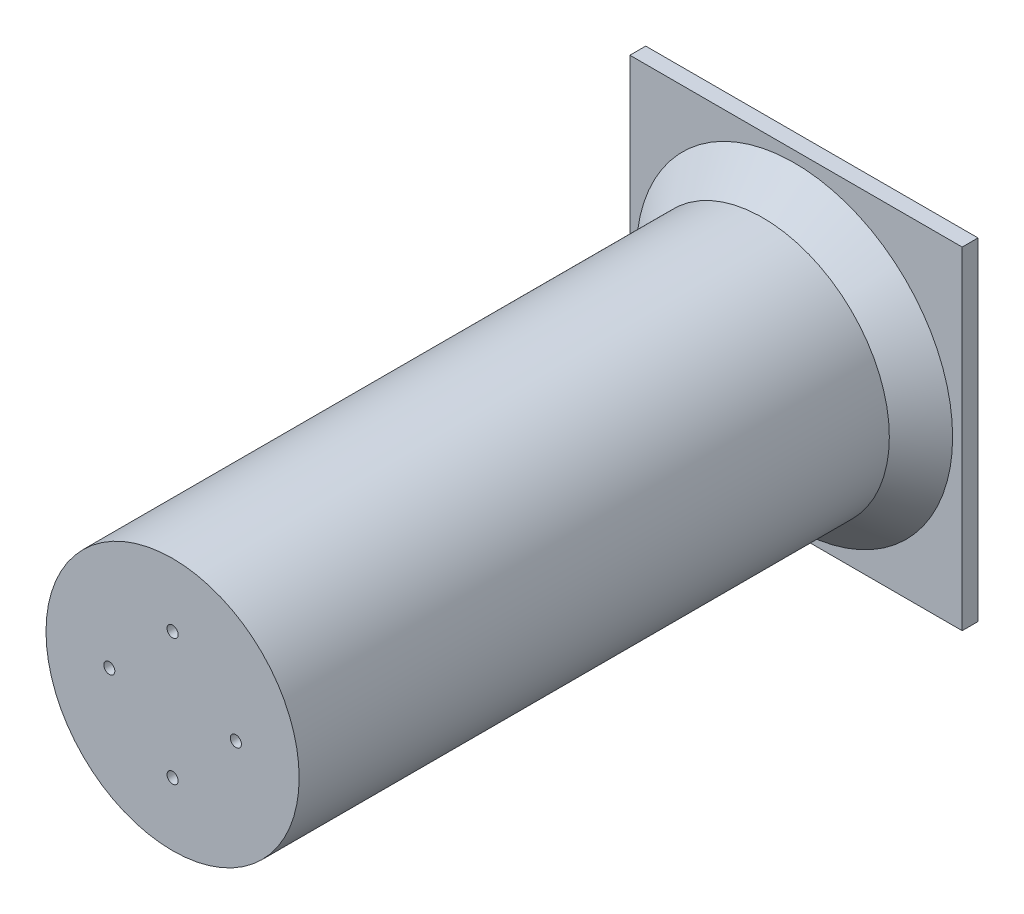
SolidWorks part; units mm, degrees
ref_plane "Alzado" through (0, 0, 0) normal (0, 0, 1) x (1, 0, 0)
ref_plane "Planta" through (0, 0, 0) normal (0, 1, 0) x (1, 0, 0)
ref_plane "Vista lateral" through (0, 0, 0) normal (1, 0, 0) x (0, 0, -1)
sketch "Croquis1" plane through (0, 0, 0) normal (0, 0, 1) x (1, 0, 0)
  line L1 (-117.2917, 97.7627) -> (131.4683, 97.7627)
  line L2 (-117.2917, 97.7627) -> (-117.2917, -97.2373)
  line L3 (-117.2917, -97.2373) -> (131.4683, -97.2373)
  line L4 (131.4683, 97.7627) -> (131.4683, -97.2373)
  dimension "D1" = 248.76
  dimension "D2" = 195
extrude "Saliente-Extruir1" add sketch "Croquis1" along normal blind 5
sketch "Croquis2" plane through (0, 0, 5) normal (0, 0, 1) x (1, 0, 0)
  line L0 (-117.2917, 0.2627) -> (131.4683, 0.2627) construction
  line L1 (-117.2917, 97.7627) -> (-117.2917, -97.2373) construction
  line L2 (131.4683, -97.2373) -> (131.4683, 97.7627) construction
  line L3 (-117.2917, -97.2373) -> (-69.2917, -97.2373)
  line L4 (-117.2917, -97.2373) -> (131.4683, -97.2373) construction
  line L5 (-69.2917, -97.2373) -> (-69.2917, -67.2373)
  line L6 (-69.2917, -67.2373) -> (-117.2917, -67.2373)
  line L7 (-117.2917, -67.2373) -> (-117.2917, -97.2373)
  line L8 (131.4683, 67.7627) -> (101.4683, 67.7627)
  line L9 (131.4683, -97.2373) -> (101.4683, -97.2373)
  line L10 (131.4683, -97.2373) -> (131.4683, -67.2373)
  line L11 (131.4683, -67.2373) -> (101.4683, -67.2373)
  line L12 (101.4683, -97.2373) -> (101.4683, -67.2373)
  line L13 (101.4683, 97.7627) -> (101.4683, 67.7627)
  line L14 (131.4683, 97.7627) -> (101.4683, 97.7627)
  line L15 (131.4683, 97.7627) -> (131.4683, 67.7627)
  line L16 (-69.2917, 67.7627) -> (-117.2917, 67.7627)
  line L17 (-69.2917, 97.7627) -> (-69.2917, 67.7627)
  line L18 (-117.2917, 97.7627) -> (-69.2917, 97.7627)
  line L19 (-117.2917, 67.7627) -> (-117.2917, 97.7627)
  dimension "D1" = 48
  dimension "D2" = 30
  dimension "D3" = 30
  dimension "D4" = 30
extrude "Cortar-Extruir1" cut sketch "Croquis2" against normal blind 2
sketch "Croquis3" plane through (0, 0, 5) normal (0, 0, 1) x (1, 0, 0)
  line L0 (-69.2917, 97.7627) -> (-117.2917, 97.7627) construction
  line L1 (116.4683, 83.7627) -> (116.4683, 67.7627) construction
  line L3 (116.4683, -83.2373) -> (116.4683, -67.2373) construction
  line L5 (131.4683, -67.2373) -> (101.4683, -67.2373) construction
  line L6 (101.4683, 67.7627) -> (131.4683, 67.7627) construction
  line L7 (-93.2917, 83.7627) -> (-93.2917, 67.7627) construction
  line L8 (-117.2917, 67.7627) -> (-69.2917, 67.7627) construction
  line L9 (-93.2917, -83.2373) -> (-93.2917, -67.2373) construction
  line L10 (-69.2917, -67.2373) -> (-117.2917, -67.2373) construction
  circle A0 centre (-93.2917, 83.7627) radius 2.375
  circle A1 centre (-93.2917, -83.2373) radius 2.375
  circle A2 centre (116.4683, 83.7627) radius 2.375
  circle A3 centre (116.4683, -83.2373) radius 2.375
  dimension "D2" = 4.75
  dimension "D3" = 4.75
  dimension "D5" = 4.75
  dimension "D6" = 4.75
  dimension "D1" = 14
  dimension "D4" = 14
  dimension "D7" = 209.76
  dimension "D8" = 16
  dimension "D9" = 16
extrude "Cortar-Extruir2" cut sketch "Croquis3" against normal blind 10
sketch "Croquis4" plane through (0, 0, 0) normal (0, 0, -1) x (-1, 0, 0)
  line L7 (-131.4683, 97.7627) -> (117.2917, 97.7627) construction
  line L9 (117.2917, 97.7627) -> (117.2917, -97.2373) construction
  circle A0 centre (55.1017, 0.2627) radius 40
  dimension "D3" = 80
  dimension "D1" = 62.19
  dimension "D2" = 97.5
extrude "Saliente-Extruir2" add sketch "Croquis4" along normal blind 196.5 contours A0
sketch "Croquis5" plane through (0, 0, 0) normal (0, 0, -1) x (-1, 0, 0)
  line L0 (-131.4683, 0.2627) -> (117.2917, 0.2627) construction
  line L1 (-131.4683, -97.2373) -> (-131.4683, 97.7627) construction
  line L2 (117.2917, 97.7627) -> (117.2917, -97.2373) construction
  circle A0 centre (-76.9683, 0.2627) radius 12.5
  dimension "D1" = 25
  dimension "D2" = 54.5
extrude "Cortar-Extruir3" cut sketch "Croquis5" against normal blind 10
sketch "Croquis6" plane through (0, 0, 0) normal (0, 0, -1) x (-1, 0, 0)
  line L0 (-131.4683, 97.7627) -> (117.2917, 97.7627) construction
  line L1 (-7.0883, 97.7627) -> (-7.0883, -97.2373)
  line L2 (117.2917, -97.2373) -> (-131.4683, -97.2373) construction
  line L3 (-7.0883, 97.7627) -> (117.2917, 97.7627)
  line L4 (117.2917, 97.7627) -> (117.2917, -97.2373)
  line L5 (117.2917, -97.2373) -> (-7.0883, -97.2373)
  line L6 (-131.4683, 0.2627) -> (56.0317, 0.2627)
  line L7 (-131.4683, -97.2373) -> (-131.4683, 97.7627) construction
  circle A1 centre (56.0317, 0.2627) radius 100
  dimension "D1" = 200
  dimension "D2" = 187.5
sketch "Croquis9" plane through (0, 97.7627, 0) normal (0, 1, 0) x (1, 0, 0)
  line L0 (7.0883, 0) -> (7.0883, -5)
  line L1 (131.4683, 0) -> (-117.2917, 0) construction
  line L2 (101.4683, -5) -> (-69.2917, -5) construction
ref_plane "Plano3" through (7.0883, 0, 0) normal (1, 0, 0) x (0, 0, -1)
sketch "Croquis12" plane through (7.0883, 0, 0) normal (1, 0, 0) x (0, 0, -1)
  line L0 (0, 97.7627) -> (0, 67.7627)
  line L1 (0, 67.7627) -> (12, 67.7627)
  line L2 (12, 67.7627) -> (12, 97.7627)
  line L3 (12, 97.7627) -> (0, 97.7627)
  line L4 (0, -97.2373) -> (12, -97.2373)
  line L5 (12, -97.2373) -> (12, -67.2373)
  line L6 (12, -67.2373) -> (0, -67.2373)
  line L7 (0, -67.2373) -> (0, -97.2373)
  dimension "D1" = 30
  dimension "D2" = 12
  dimension "D3" = 30
  dimension "D4" = 12
extrude "Saliente-Extruir3" add sketch "Croquis12" along normal mid plane 8
fillet "Redondeo1" radius 10 2 edges at (7.0883, -67.2373, 0) (7.0883, 67.7627, 0)
fillet "Redondeo2" radius 10 2 edges at (7.0883, 67.7627, -12) (7.0883, -67.2373, -12)
fillet "Redondeo3" radius 10 2 edges at (7.0883, -97.2373, -12) (7.0883, 97.7627, -12)
sketch "Croquis13" plane through (11.0883, 0, 0) normal (1, 0, 0) x (0, 0, -1)
  line L0 (-5, 0.2627) -> (196.5, 0.2627) construction
  line L1 (-5, -67.2373) -> (-5, 67.7627) construction
  line L2 (196.5, -39.7373) -> (196.5, 40.2627) construction
  line L3 (6, 87.7627) -> (12, 87.7627) construction
  line L4 (6, 87.7627) -> (6, 77.7627) construction
  circle A0 centre (6, 87.7627) radius 1.625
  circle A1 centre (6, 77.7627) radius 1.625
  circle A2 centre (6, -77.2373) radius 1.625
  circle A3 centre (6, -87.2373) radius 1.625
  dimension "D3" = 3.25
  dimension "D4" = 3.25
  dimension "D1" = 6
extrude "Cortar-Extruir5" cut sketch "Croquis13" against normal through all both and the other way through all
sketch "Croquis14" plane through (0, 0, 0) normal (0, 0, -1) x (-1, 0, 0)
  line L0 (-7.0883, 97.7627) -> (-7.0883, -97.2373)
  line L1 (-7.0883, 97.7627) -> (117.2917, 97.7627)
  line L2 (117.2917, 97.7627) -> (117.2917, -97.2373)
  line L3 (117.2917, -97.2373) -> (-7.0883, -97.2373)
sketch "Croquis15" plane through (0, 0, 5) normal (0, 0, 1) x (1, 0, 0)
  line L0 (111.4683, 67.7627) -> (131.4683, 67.7627)
  line L1 (111.4683, 67.7627) -> (111.4683, 60.0127)
  line L2 (131.4683, -67.2373) -> (101.4683, -67.2373) construction
  line L3 (111.4683, -67.2373) -> (111.4683, -59.4873)
  line L4 (111.4683, -59.4873) -> (125.2183, -59.4873)
  line L5 (125.2183, -59.4873) -> (125.2183, 60.0127)
  line L6 (111.4683, 60.0127) -> (125.2183, 60.0127)
  line L7 (111.4683, -67.2373) -> (131.4683, -67.2373)
  line L10 (131.4683, -67.2373) -> (131.4683, 67.7627)
  dimension "D1" = 119.5
  dimension "D2" = 7.75
  dimension "D3" = 13.75
extrude "Cortar-Extruir7" cut sketch "Croquis15" against normal blind 2
sketch "Croquis16" plane through (0, 0, 5) normal (0, 0, 1) x (1, 0, 0)
  circle A1 centre (-55.1017, 20.2627) radius 1.75
  circle A2 centre (-35.1017, 0.2627) radius 1.75
  circle A3 centre (-55.1017, -19.7373) radius 1.75
  circle A4 centre (-75.1017, 0.2627) radius 1.75
  dimension "D3" = 3.5
  dimension "D4" = 4
extrude "Cortar-Extruir9" cut sketch "Croquis16" against normal blind 20
sketch "Croquis20" plane through (0, -97.2373, 0) normal (0, -1, 0) x (1, 0, 0)
  line L0 (-117.2917, 10.5315) -> (-117.2917, 0)
  line L1 (-117.2917, 0) -> (3.0883, 0)
  line L2 (3.0883, 0) -> (3.0883, -12)
  line L3 (3.0883, -12) -> (11.0883, -12)
  line L4 (11.0883, -12) -> (11.0883, 0)
  line L5 (11.0883, 0) -> (131.4683, 0)
  line L6 (131.4683, 0) -> (131.4683, 10.5315)
  line L7 (131.4683, 10.5315) -> (-117.2917, 10.5315)
extrude "Cortar-Extruir17" cut sketch "Croquis20" against normal through all both and the other way through all
sketch "Croquis21" plane through (0, 0, -196.5) normal (0, 0, -1) x (-1, 0, 0)
  line L1 (2.0835, -51.2668) -> (107.0835, -51.2668)
  line L2 (2.0835, -51.2668) -> (2.0835, 53.7332)
  line L3 (2.0835, 53.7332) -> (107.0835, 53.7332)
  line L4 (107.0835, -51.2668) -> (107.0835, 53.7332)
  line L5 (2.0835, -51.2668) -> (107.0835, 53.7332) construction
  line L6 (2.0835, 53.7332) -> (107.0835, -51.2668) construction
  point P0 (54.5835, 1.2332)
  dimension "D1" = 105
  dimension "D2" = 105
extrude "Saliente-Extruir4" add sketch "Croquis21" along normal blind 5
chamfer "Chaflán1" distance 10 angle 45 1 edges at (-95.1017, 0.2627, -196.5)
